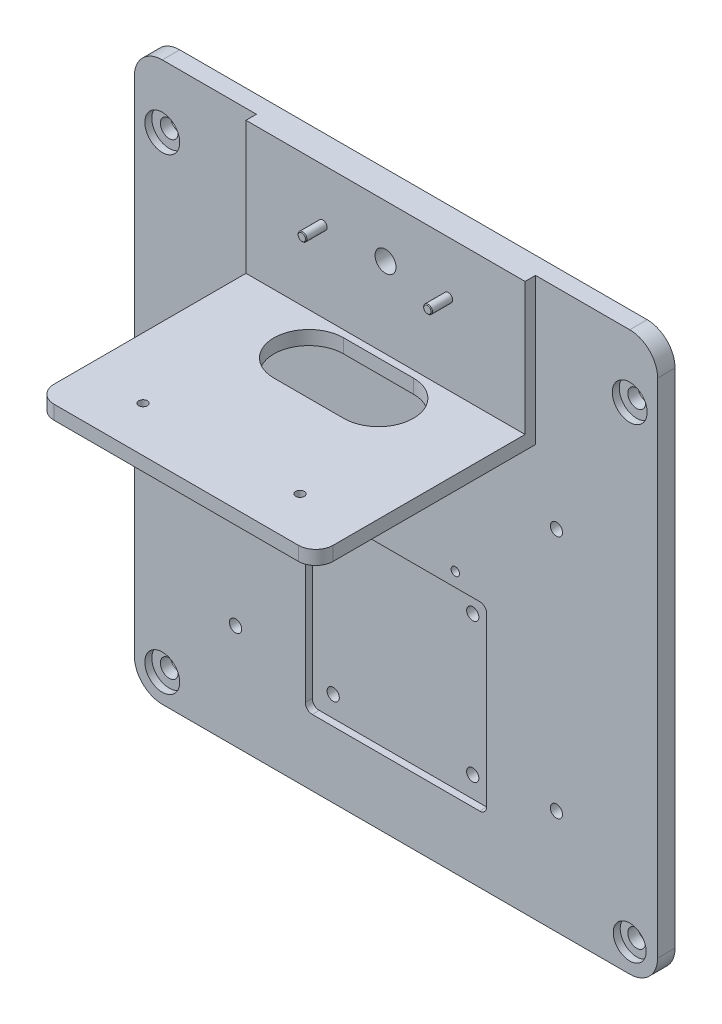
SolidWorks part; units mm, degrees
ref_plane "前视基准面" through (0, 0, 0) normal (0, 0, 1) x (1, 0, 0)
ref_plane "上视基准面" through (0, 0, 0) normal (0, 1, 0) x (1, 0, 0)
ref_plane "右视基准面" through (0, 0, 0) normal (1, 0, 0) x (0, 0, -1)
sketch "草图1" plane through (0, 0, 0) normal (0, 0, 1) x (1, 0, 0)
  line L1 (-75, 80) -> (75, 80)
  line L2 (-75, 80) -> (-75, -80)
  line L3 (-75, -80) -> (75, -80)
  line L4 (75, 80) -> (75, -80)
  line L5 (0, -80) -> (0, 80) construction
  line L6 (-75, 0) -> (75, 0) construction
  point P0 (0, 0)
  dimension "D1" = 160
  dimension "D2" = 150
extrude "凸台-拉伸1" add sketch "草图1" along normal blind 5
sketch "草图2" plane through (0, 0, 5) normal (0, 0, 1) x (1, 0, 0)
  line L0 (-75, -80) -> (75, -80) construction
  line L1 (-20, -15) -> (20, -15) construction
  line L2 (-20, -15) -> (-20, -55) construction
  line L3 (-20, -55) -> (20, -55) construction
  line L4 (20, -15) -> (20, -55) construction
  line L5 (0, -55) -> (0, -15) construction
  line L6 (-20, -35) -> (20, -35) construction
  circle A0 centre (-20, -15) radius 1.75
  circle A1 centre (20, -15) radius 1.75
  circle A2 centre (20, -55) radius 1.75
  circle A3 centre (-20, -55) radius 1.75
  point P0 (0, 0)
  dimension "D2" = 3.5
  dimension "D1" = 40
  dimension "D3" = 25
extrude "切除-拉伸1" cut sketch "草图2" against normal through all
sketch "草图3" plane through (0, 0, 5) normal (0, 0, 1) x (1, 0, 0)
  line L0 (-75, -80) -> (75, -80) construction
  line L1 (46, 20) -> (-46, 20) construction
  line L2 (46, 20) -> (46, -50) construction
  line L3 (46, -50) -> (-46, -50) construction
  line L4 (-46, 20) -> (-46, -50) construction
  line L5 (0, -50) -> (0, 20) construction
  line L6 (46, -15) -> (-46, -15) construction
  circle A0 centre (46, 20) radius 1.75
  circle A1 centre (46, -50) radius 1.75
  circle A2 centre (-46, -50) radius 1.75
  circle A3 centre (-46, 20) radius 1.75
  point P0 (0, -15)
  dimension "D4" = 3.5
  dimension "D1" = 70
  dimension "D2" = 92
  dimension "D3" = 30
extrude "切除-拉伸2" cut sketch "草图3" against normal through all
sketch "草图4" plane through (0, 0, 5) normal (0, 0, 1) x (1, 0, 0)
  line L4 (75, -80) -> (75, 80) construction
  line L5 (-67, 72) -> (67, 72) construction
  line L6 (-67, 72) -> (-67, -72) construction
  line L7 (-67, -72) -> (67, -72) construction
  line L12 (67, 72) -> (67, -72) construction
  line L13 (0, -72) -> (0, 72) construction
  line L14 (-67, 0) -> (67, 0) construction
  line L15 (75, 80) -> (-75, 80) construction
  circle A4 centre (-67, 72) radius 2.55 construction
  circle A5 centre (-67, -72) radius 2.55
  circle A6 centre (67, -72) radius 2.55
  circle A7 centre (67, 72) radius 2.55 construction
  circle A8 centre (-67, 62) radius 2.55
  circle A9 centre (67, 62) radius 2.55
  point P0 (0, 0)
  dimension "D3" = 5.1
  dimension "D4" = 134
  dimension "D1" = 8
  dimension "D2" = 8
extrude "切除-拉伸3" cut sketch "草图4" against normal blind 7
fillet "圆角1" radius 8 4 edges at (-75, -80, 2.5) (75, -80, 2.5) (75, 80, 2.5) (-75, 80, 2.5)
sketch "草图5" plane through (0, 0, 5) normal (0, 0, 1) x (1, 0, 0)
  line L0 (-10, 65) -> (10, 65) construction
  line L1 (-10, 66.6) -> (10, 66.6) construction
  line L2 (-10, 63.4) -> (10, 63.4) construction
  line L3 (0, 80) -> (0, 65) construction
  line L4 (67, 80) -> (-67, 80) construction
  arc A0 (-10, 66.6) -> (-10, 63.4) centre (-10, 65) ccw construction
  arc A1 (10, 63.4) -> (10, 66.6) centre (10, 65) ccw construction
  circle A2 centre (0, 65) radius 2.55
  point P2 (0, 65)
  dimension "D1" = 1.6
  dimension "D3" = 5.1
  dimension "D2" = 15
  dimension "20" = 20
extrude "切除-拉伸4" cut sketch "草图5" against normal through all
sketch "草图6" plane through (0, 0, 0) normal (1, 0, 0) x (0, 0, -1)
  line L0 (-5, 80) -> (-5, 38)
  line L1 (-5, 72) -> (-5, -72) construction
  line L2 (-5, 38) -> (-68, 38)
  line L3 (-68, 38) -> (-68, 42)
  line L4 (-68, 42) -> (-8, 42)
  line L5 (-8, 42) -> (-8, 80)
  line L7 (0, 80) -> (-5, 80) construction
  line L8 (-8, 80) -> (-5, 80)
  dimension "D1" = 3
  dimension "D2" = 4
  dimension "D3" = 60
  dimension "D4" = 42
extrude "凸台-拉伸2" add sketch "草图6" along normal mid plane 80
sketch "草图7" plane through (0, 0, 5) normal (0, 0, 1) x (1, 0, 0)
  circle A0 centre (67, 62) radius 5
  circle A1 centre (-67, 62) radius 5
  circle A3 centre (67, -72) radius 4.7182
  circle A4 centre (-67, -72) radius 5
  dimension "D1" = 10
  dimension "D2" = 10
extrude "切除-拉伸5" cut sketch "草图7" against normal blind 2
sketch "草图9" plane through (0, 42, 0) normal (0, 1, 0) x (1, 0, 0)
  line L0 (67, -5) -> (40, -5) construction
  line L1 (0, -31.9) -> (0, 31.9) construction
  circle A0 centre (22.5, -55) radius 1.25
  circle A1 centre (-22.5, -55) radius 1.25
  dimension "D1" = 50
  dimension "D2" = 2.5
  dimension "D3" = 22.5
extrude "切除-拉伸6" cut sketch "草图9" against normal through all both and the other way through all
sketch "草图10" plane through (0, 42, 0) normal (0, 1, 0) x (1, 0, 0)
  line L0 (10, -20) -> (-10, -20) construction
  line L1 (0, -31.9) -> (0, 31.9) construction
  line L2 (10, -30) -> (-10, -30)
  line L3 (10, -10) -> (-10, -10)
  line L4 (40, -8) -> (-40, -8) construction
  line L5 (40, -8) -> (-40, -8) construction
  arc A0 (10, -30) -> (10, -10) centre (10, -20) ccw
  arc A1 (-10, -10) -> (-10, -30) centre (-10, -20) ccw
  point P4 (0, -20)
  dimension "D1" = 2
  dimension "D2" = 20
  dimension "D3" = 20
extrude "切除-拉伸7" cut sketch "草图10" against normal through all both and the other way through all
sketch "草图11" plane through (0, 0, 0) normal (0, 0, -1) x (-1, 0, 0)
  circle A0 centre (0, 65) radius 3
  dimension "D1" = 6
extrude "切除-拉伸8" cut sketch "草图11" against normal through all
sketch "草图12" plane through (0, 0, 8) normal (0, 0, 1) x (1, 0, 0)
  line L0 (0, 65) -> (40, 65) construction
  line L1 (40, 38) -> (40, 80) construction
  line L2 (0, -31.9) -> (0, 31.9) construction
  circle A0 centre (18, 65) radius 1.25
  circle A1 centre (-18, 65) radius 1.25
  dimension "D1" = 18
  dimension "D2" = 2.5
extrude "凸台-拉伸3" add sketch "草图12" along normal blind 6
sketch "草图13" plane through (0, 0, 5) normal (0, 0, 1) x (1, 0, 0)
  line L0 (-20, -15) -> (20, -55) construction
  line L2 (-26, -9) -> (26, -9)
  line L3 (-26, -9) -> (-26, -61)
  line L4 (-26, -61) -> (26, -61)
  line L5 (26, -9) -> (26, -61)
  line L6 (-26, -9) -> (26, -61) construction
  line L7 (-26, -61) -> (26, -9) construction
  circle A0 centre (20, -15) radius 1.75 construction
  point P4 (0, -35)
  dimension "D1" = 6
extrude "切除-拉伸9" cut sketch "草图13" against normal blind 2
sketch "草图14" plane through (0, 0, 0) normal (0, 0, -1) x (-1, 0, 0)
  line L1 (17, -5) -> (-17, -5) construction
  line L2 (17, -5) -> (17, 56) construction
  line L3 (17, 56) -> (-17, 56) construction
  line L4 (-17, -5) -> (-17, 56) construction
  line L5 (17, -5) -> (-17, 56) construction
  line L6 (17, 56) -> (-17, -5) construction
  circle A0 centre (-20, -15) radius 1.75 construction
  circle A1 centre (17, -5) radius 1.2
  circle A2 centre (17, 56) radius 1.2
  circle A3 centre (-17, 56) radius 1.2
  circle A4 centre (-17, -5) radius 1.2
  point P0 (0, 25.5)
  dimension "D3" = 10
  dimension "D4" = 2.4
  dimension "D1" = 34
  dimension "D2" = 61
extrude "切除-拉伸10" cut sketch "草图14" against normal blind 5 and the other way through all
fillet "圆角2" radius 2 4 edges at (26, -61, 4) (-26, -61, 4) (-26, -9, 4) (26, -9, 4)
fillet "圆角3" radius 5 2 edges at (40, 40, 68) (-40, 40, 68)
chamfer "倒角1" distance 0.2 angle 45 2 edges at (19.25, 65, 14) (-19.25, 65, 14)
